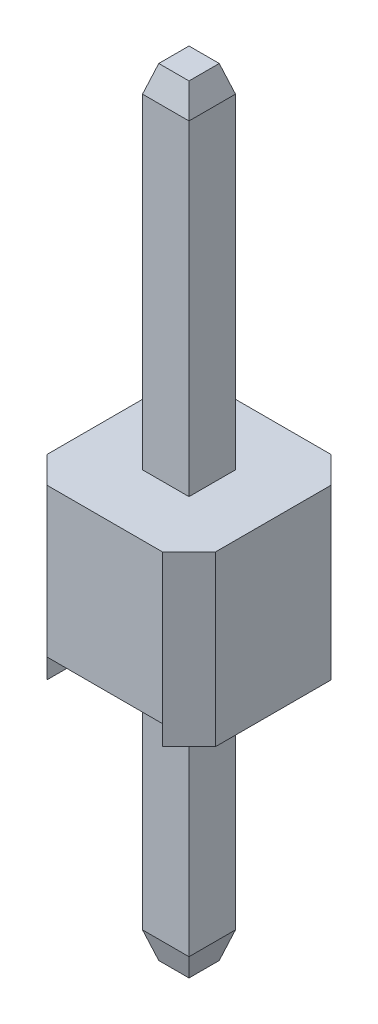
SolidWorks part; units mm, degrees
ref_plane "Front Plane" through (0, 0, 0) normal (0, 0, 1) x (1, 0, 0)
ref_plane "Top Plane" through (0, 0, 0) normal (0, 1, 0) x (1, 0, 0)
ref_plane "Right Plane" through (0, 0, 0) normal (1, 0, 0) x (0, 0, -1)
sketch "Sketch1" plane through (0, 0, 0) normal (0, 1, 0) x (1, 0, 0)
  line L1 (-1.27, 1.27) -> (1.27, 1.27)
  line L2 (-1.27, 1.27) -> (-1.27, -1.27)
  line L3 (-1.27, -1.27) -> (1.27, -1.27)
  line L4 (1.27, 1.27) -> (1.27, -1.27)
  line L5 (-1.27, 1.27) -> (1.27, -1.27) construction
  line L6 (-1.27, -1.27) -> (1.27, 1.27) construction
  point P0 (0, 0)
  dimension "D1" = 2.54
  dimension "D2" = 2.54
extrude "Boss-Extrude1" add sketch "Sketch1" along normal blind 2.54
chamfer "Chamfer1" distance 0.4 angle 45 4 edges at (-1.27, 1.27, -1.27) (1.27, 1.27, -1.27) (-1.27, 1.27, 1.27) (1.27, 1.27, 1.27)
sketch "Sketch2" plane through (0, 0, 0) normal (0, -1, 0) x (1, 0, 0)
  line L1 (-0.87, 1.27) -> (0.87, 1.27)
  line L2 (-0.87, 1.27) -> (-0.87, -1.27)
  line L3 (-0.87, -1.27) -> (0.87, -1.27)
  line L4 (0.87, 1.27) -> (0.87, -1.27)
extrude "Cut-Extrude1" cut sketch "Sketch2" against normal blind 0.3
sketch "Sketch3" plane through (0, 2.54, 0) normal (0, 1, 0) x (1, 0, 0)
  line L1 (0.35, 0.35) -> (-0.35, 0.35)
  line L2 (0.35, 0.35) -> (0.35, -0.35)
  line L3 (0.35, -0.35) -> (-0.35, -0.35)
  line L4 (-0.35, 0.35) -> (-0.35, -0.35)
  line L5 (0.35, 0.35) -> (-0.35, -0.35) construction
  line L6 (0.35, -0.35) -> (-0.35, 0.35) construction
  point P0 (0, 0)
  dimension "D1" = 0.7
  dimension "D2" = 0.7
extrude "Boss-Extrude2" add sketch "Sketch3" along normal blind 5.3
sketch "Sketch4" plane through (0, 0.3, 0) normal (0, -1, 0) x (1, 0, 0)
  line L0 (-0.35, 0.35) -> (0.35, 0.35) construction
  line L1 (-0.35, 0.35) -> (0.35, 0.35)
  line L2 (-0.35, 0.35) -> (-0.35, -0.35)
  line L3 (-0.35, -0.35) -> (0.35, -0.35)
  line L4 (0.35, 0.35) -> (0.35, -0.35)
  line L5 (-0.35, 0.35) -> (0.35, -0.35) construction
  line L6 (-0.35, -0.35) -> (0.35, 0.35) construction
  line L7 (0.35, 0.35) -> (0.35, -0.35) construction
  point P0 (0, 0)
extrude "Boss-Extrude3" add sketch "Sketch4" along normal offset from surface (4.16 mm away) 11.7 up to face at (0, 7.84, 0)
chamfer "Chamfer2" distance 0.4 angle 17 8 edges at (0, 7.84, -0.35) (-0.35, 7.84, 0) (0.35, 7.84, 0) (0, 7.84, 0.35) (0, -3.86, -0.35) (-0.35, -3.86, 0) (0.35, -3.86, 0) (0, -3.86, 0.35)
